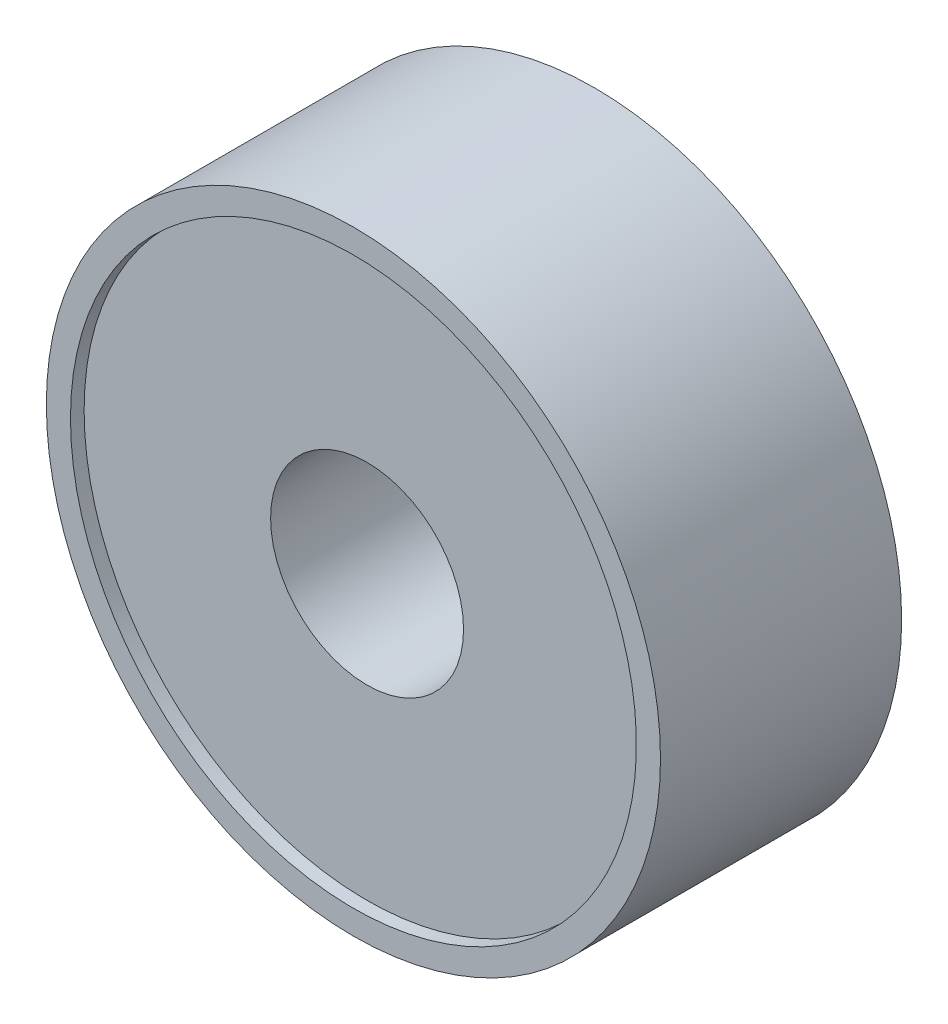
SolidWorks part; units mm, degrees
ref_plane "Front Plane" through (0, 0, 0) normal (0, 0, 1) x (1, 0, 0)
ref_plane "Top Plane" through (0, 0, 0) normal (0, 1, 0) x (1, 0, 0)
ref_plane "Right Plane" through (0, 0, 0) normal (1, 0, 0) x (0, 0, -1)
sketch "Sketch1" plane through (0, 0, 0) normal (1, 0, 0) x (0, 0, -1)
  line L0 (0, 0) -> (-50, 0) construction
  line L1 (0, -3.3213) -> (0, -48.514) construction
  line L5 (-19.05, -48.514) -> (-19.05, -44.704)
  line L7 (-16.8947, -44.704) -> (-16.8947, -15.24)
  line L17 (-19.05, -48.514) -> (19.05, -48.514)
  line L18 (-19.05, -44.704) -> (-16.8947, -44.704)
  line L19 (-16.8947, -15.24) -> (16.8947, -15.24)
  line L20 (19.05, -44.704) -> (16.8947, -44.704)
  line L21 (16.8947, -44.704) -> (16.8947, -15.24)
  line L22 (19.05, -48.514) -> (19.05, -44.704)
  point P9 (0, -15.24)
  point P17 (0, -15.24)
  dimension "D1" = 15.24
  dimension "D2" = 38.1
  dimension "D4" = 3.81
revolve "Revolve4" add sketch "Sketch1" angle 360 about L0
sketch "Sketch2" plane through (0, 0, 16.8947) normal (0, 0, 1) x (1, 0, 0)
  line L0 (0, 0) -> (0, 38.1) construction
  circle A0 centre (0, 0) radius 38.1
  circle A1 centre (0, 0) radius 25.4
  point P4 (0, 25.4)
  point P6 (0, 15.1888)
  dimension "D1" = 38.1
  dimension "D2" = 25.4
  dimension "D3" = 15.1888
